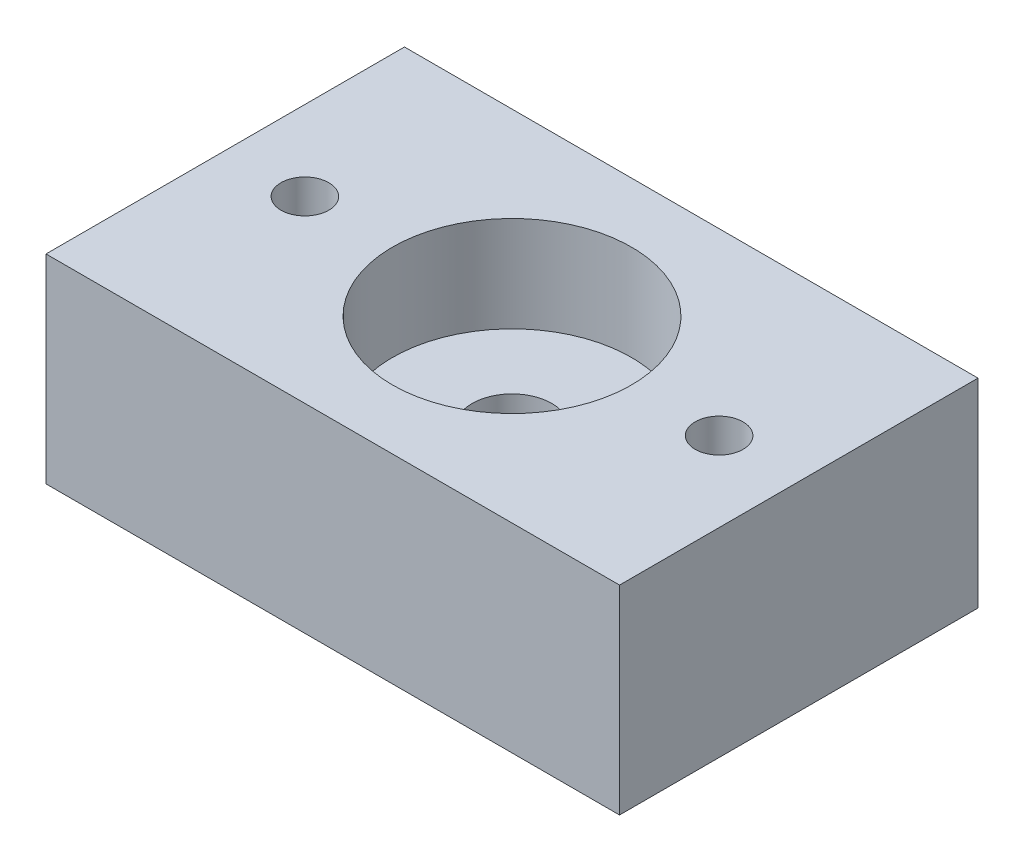
SolidWorks part; units mm, degrees
ref_plane "Front Plane" through (0, 0, 0) normal (0, 0, 1) x (1, 0, 0)
ref_plane "Top Plane" through (0, 0, 0) normal (0, 1, 0) x (1, 0, 0)
ref_plane "Right Plane" through (0, 0, 0) normal (1, 0, 0) x (0, 0, -1)
sketch "Sketch1" plane through (0, 0, 0) normal (0, 1, 0) x (1, 0, 0)
  line L1 (-36, 22.5) -> (36, 22.5)
  line L2 (-36, 22.5) -> (-36, -22.5)
  line L3 (-36, -22.5) -> (36, -22.5)
  line L4 (36, 22.5) -> (36, -22.5)
  line L5 (-36, 22.5) -> (36, -22.5) construction
  line L6 (-36, -22.5) -> (36, 22.5) construction
  point P0 (0, 0)
  point P5 (0, 0)
  dimension "D1" = 72
  dimension "D2" = 45
extrude "Boss-Extrude1" add sketch "Sketch1" along normal blind 25
sketch "Sketch2" plane through (0, 25, 0) normal (0, 1, 0) x (1, 0, 0)
  circle A0 centre (0, 0) radius 5
  dimension "D1" = 10
extrude "Cut-Extrude1" cut sketch "Sketch2" against normal through all
sketch "Sketch3" plane through (0, 25, 0) normal (0, 1, 0) x (1, 0, 0)
  line L0 (0, 22.5) -> (0, -22.5) construction
  line L1 (36, 22.5) -> (-36, 22.5) construction
  line L2 (-36, -22.5) -> (36, -22.5) construction
  circle A0 centre (-26, 0) radius 3
  circle A2 centre (26, 0) radius 3
  point P9 (0, 0)
  dimension "D1" = 6
  dimension "D2" = 26
extrude "Cut-Extrude2" cut sketch "Sketch3" against normal through all
sketch "Sketch4" plane through (0, 25, 0) normal (0, 1, 0) x (1, 0, 0)
  circle A0 centre (0, 0) radius 15
  dimension "D1" = 30
extrude "Cut-Extrude3" cut sketch "Sketch4" against normal blind 12
